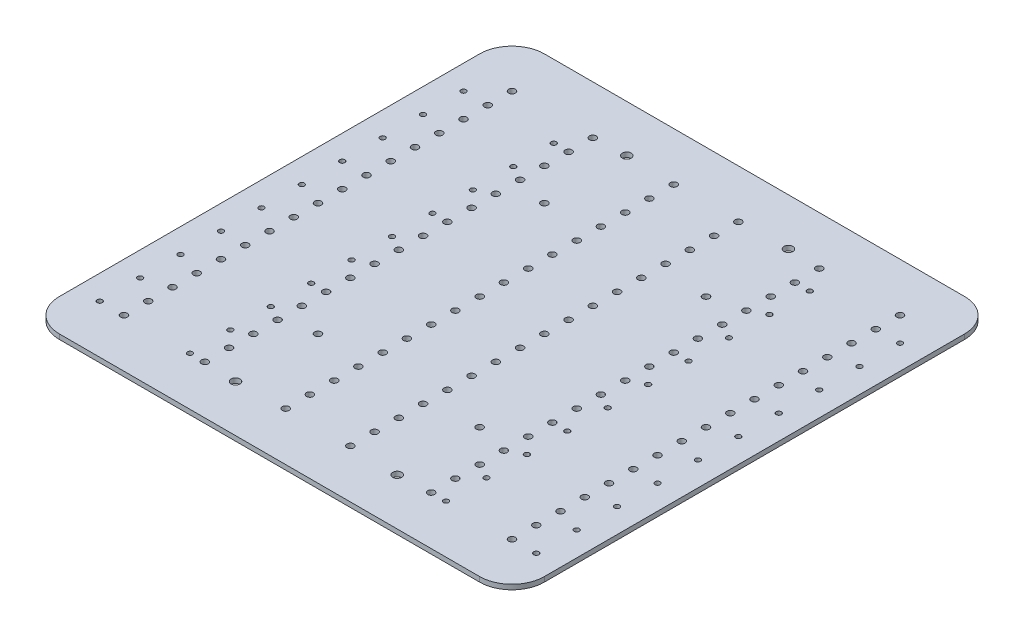
SolidWorks part; units mm, degrees
material "玻璃"
ref_plane "前视基准面" through (0, 0, 0) normal (0, 0, 1) x (1, 0, 0)
ref_plane "上视基准面" through (0, 0, 0) normal (0, 1, 0) x (1, 0, 0)
ref_plane "右视基准面" through (0, 0, 0) normal (1, 0, 0) x (0, 0, -1)
sketch "草图2" plane through (0, 0, 0) normal (0, 1, 0) x (1, 0, 0)
  line L1 (-150, -150) -> (150, -150)
  line L2 (-150, -150) -> (-150, 150)
  line L3 (-150, 150) -> (150, 150)
  line L4 (150, -150) -> (150, 150)
  line L5 (-150, -150) -> (150, 150) construction
  line L6 (-150, 150) -> (150, -150) construction
  point P0 (0, 0)
  dimension "D1" = 300
  dimension "D2" = 300
extrude "凸台-拉伸1" add sketch "草图2" along normal blind 3
fillet "圆角1" radius 20 4 edges at (150, 1.5, -150) (150, 1.5, 150) (-150, 1.5, -150) (-150, 1.5, 150)
sketch "草图3" plane through (0, 0, 0) normal (0, -1, 0) x (1, 0, 0)
  line L0 (-130, 150) -> (130, 150) construction
  line L1 (-150, -130) -> (-150, 130) construction
  circle A0 centre (-50, 70) radius 2.1
  dimension "D1" = 4.2
  dimension "D2" = 80
  dimension "D3" = 100
extrude "切除-拉伸1" cut sketch "草图3" against normal through all
ref_plane "基准面1" through (0, 0, 0) normal (-1, 0, 0) x (0, 0, 1)
ref_plane "基准面2" through (0, 0, 0) normal (0, 0, -1) x (-1, 0, 0)
mirror "镜向1" about plane through (0, 0, 0) normal (-1, 0, 0) of "切除-拉伸1"
mirror "镜向2" about plane through (0, 0, 0) normal (0, 0, -1) of "镜向1", "切除-拉伸1"
sketch "草图4" plane through (0, 3, 0) normal (0, 1, 0) x (1, 0, 0)
  line L1 (-130, -150) -> (130, -150) construction
  circle A0 centre (-50, -121) radius 2.75
  circle A1 centre (-50, -70) radius 2.1 construction
  dimension "D1" = 5.5
  dimension "D2" = 29
  dimension "D3" = 51
extrude "切除-拉伸2" cut sketch "草图4" against normal through all
mirror "镜向3" about plane through (0, 0, 0) normal (-1, 0, 0) of "切除-拉伸2"
mirror "镜向4" about plane through (0, 0, 0) normal (0, 0, -1) of "镜向3", "切除-拉伸2"
sketch "草图5" plane through (0, 3, 0) normal (0, 1, 0) x (1, 0, 0)
  line L0 (-150, 130) -> (-150, -130) construction
  line L1 (-130, -150) -> (130, -150) construction
  circle A0 centre (-120, -120) radius 2.1
  dimension "D1" = 4.2
  dimension "D2" = 30
  dimension "D3" = 30
extrude "切除-拉伸3" cut sketch "草图5" against normal through all
pattern_linear "阵列(线性)1" count 17 spacing 15 along (0, 0, -1) of "切除-拉伸3"
pattern_linear "阵列(线性)2" count 3 spacing 50 along (1, 0, 0) of "阵列(线性)1", "切除-拉伸3"
mirror "镜向5" about plane through (0, 0, 0) normal (-1, 0, 0) of "阵列(线性)2", "切除-拉伸3", "阵列(线性)1"
sketch "草图6" plane through (0, 3, 0) normal (0, 1, 0) x (1, 0, 0)
  line L0 (-130, -150) -> (130, -150) construction
  line L1 (-150, 130) -> (-150, -130) construction
  circle A0 centre (-135, -120) radius 1.6
  dimension "D1" = 3.2
  dimension "D2" = 30
  dimension "D3" = 15
extrude "切除-拉伸4" cut sketch "草图6" against normal through all
pattern_linear "阵列(线性)3" count 10 spacing 25 along (0, 0, -1) of "切除-拉伸4"
pattern_linear "阵列(线性)4" count 2 spacing 55.8 along (1, 0, 0) of "阵列(线性)3", "切除-拉伸4"
mirror "镜向6" about plane through (0, 0, 0) normal (-1, 0, 0) of "阵列(线性)4", "切除-拉伸4", "阵列(线性)3"
